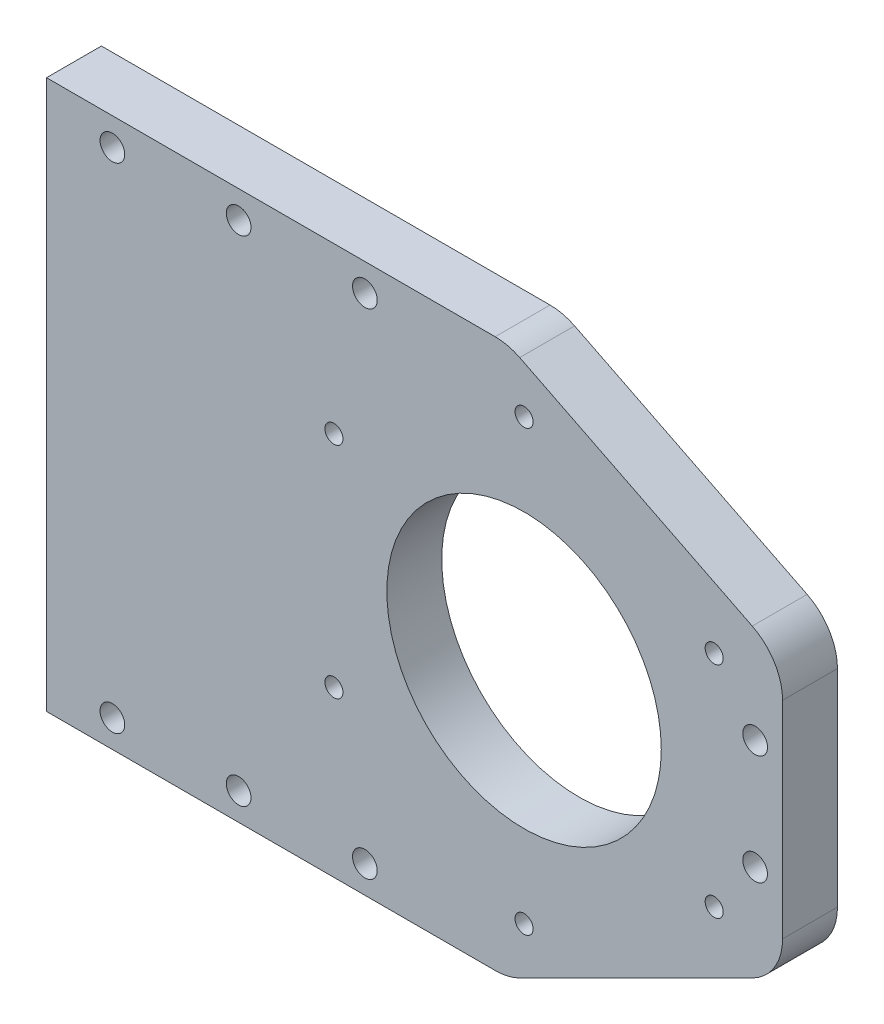
SolidWorks part; units mm, degrees
material "7079 Alloy"
ref_plane "Front Plane" through (0, 0, 0) normal (0, 0, 1) x (1, 0, 0)
ref_plane "Top Plane" through (0, 0, 0) normal (0, 1, 0) x (1, 0, 0)
ref_plane "Right Plane" through (0, 0, 0) normal (1, 0, 0) x (0, 0, -1)
sketch "Sketch1" plane through (0, 0, 0) normal (0, 0, 1) x (1, 0, 0)
  line L0 (0, 0) -> (84.1, 0) construction
  line L1 (0, -50) -> (84.1, -50)
  line L2 (84.1, 50) -> (134.1, 25)
  line L3 (0, -50) -> (0, 50)
  line L4 (0, 50) -> (84.1, 50)
  line L5 (134.1, -25) -> (134.1, 25)
  line L6 (84.1, -50) -> (134.1, -25)
  line L7 (84.1, 0) -> (84.1, -50) construction
  point P3 (134.1, 50)
  point P5 (134.1, -50)
  dimension "D1" = 134.1
  dimension "D2" = 100
  dimension "D3" = 25
  dimension "D4" = 25
extrude "Extrude1" add sketch "Sketch1" along normal blind 10
sketch "Sketch5" plane through (0, 0, 10) normal (0, 0, 1) x (1, 0, 0)
  line L0 (0, 0) -> (87, 0) construction
  circle A0 centre (87, 0) radius 25
  dimension "D2" = 50
  dimension "D1" = 87
extrude "Cut-Extrude1" cut sketch "Sketch5" against normal blind 20
sketch "Sketch6" plane through (0, 0, 0) normal (-1, 0, 0) x (0, 0, 1)
  line L0 (5, 50) -> (5, -50) construction
  line L1 (10, 50) -> (0, 50) construction
  line L2 (10, -50) -> (0, -50) construction
  line L3 (0, 0) -> (10, 0) construction
  line L4 (10, 50) -> (10, -50) construction
  circle A0 centre (5, 37.5) radius 1.65
  circle A1 centre (5, 12.5) radius 1.65
  circle A2 centre (5, -37.5) radius 1.65
  circle A3 centre (5, -12.5) radius 1.65
  dimension "D1" = 3.3
  dimension "D3" = 25
  dimension "D2" = 12.5
extrude "Cut-Extrude2" cut sketch "Sketch6" against normal blind 15
sketch "Sketch7" plane through (0, 0, 0) normal (0, 0, -1) x (-1, 0, 0)
  line L0 (0, 45) -> (-70, 45) construction
  line L1 (-84.1, 50) -> (0, 50) construction
  line L2 (0, 50) -> (0, -50) construction
  line L3 (-35, 45) -> (-35, 50) construction
  line L4 (0, 0) -> (-62, 0) construction
  circle A0 centre (-12, 45) radius 1.5
  circle A1 centre (-35, 45) radius 1.5
  circle A2 centre (-58, 45) radius 1.5
  circle A3 centre (-87, 0) radius 25 construction
  circle A4 centre (-58, -45) radius 1.5
  circle A5 centre (-35, -45) radius 1.5
  circle A6 centre (-12, -45) radius 1.5
  dimension "D2" = 3
  dimension "D1" = 12
  dimension "D3" = 23
  dimension "D4" = 5
extrude "Cut-Extrude3" cut sketch "Sketch7" against normal up to next
hole_wizard "CSK for M4 Flat Head Machine Screw1" positions "Sketch9" profile "Sketch8" countersink size "M4" standard "Ansi Metric" end condition through all
sketch "Sketch9" plane through (0, 0, 0) normal (0, 0, -1) x (-1, 0, 0)
  point P1 (-12, 45)
  point P4 (-35, 45)
  point P7 (-58, 45)
  point P10 (-12, -45)
  point P13 (-35, -45)
  point P16 (-58, -45)
sketch "Sketch8" plane through (12, 45, 0) normal (1, 0, 0) x (0, 1, 0)
  line L0 (0, 0) -> (0, 10)
  line L1 (0, 10) -> (2.25, 10)
  line L2 (2.25, 10) -> (2.25, 2.45)
  line L3 (2.25, 2.45) -> (4.7, 0)
  line L5 (4.7, 0) -> (0, 0)
  line L6 (-2.25, 2.45) -> (-4.7, 0) construction
  line L11 (0, -6.35) -> (0, 107.95) construction
  dimension "Thru Hole Dia." = 4.5
  dimension "Thru Hole Depth" = 10
  dimension "Near C'Sink Dia." = 9.4
  dimension "Near C'Sink Angle" = 90
sketch "Sketch10" plane through (0, 0, 0) normal (0, 0, -1) x (-1, 0, 0)
  line L0 (-87, 0) -> (-87, 40) construction
  circle A0 centre (-87, 0) radius 40 construction
  circle A1 centre (-87, 40) radius 1.65
  circle A2 centre (-52.359, 20) radius 1.65
  circle A3 centre (-52.359, -20) radius 1.65
  circle A4 centre (-87, -40) radius 1.65
  circle A5 centre (-121.641, -20) radius 1.65
  circle A6 centre (-121.641, 20) radius 1.65
  dimension "D2" = 3.3
  dimension "D3" = 80
  dimension "D1" = 6
extrude "Cut-Extrude4" cut sketch "Sketch10" against normal blind 10
fillet "Fillet1" radius 10 4 edges at (84.1, -50, 5) (134.1, -25, 5) (134.1, 25, 5) (84.1, 50, 5)
sketch "Sketch13" plane through (0, 0, 0) normal (0, 0, -1) x (-1, 0, 0)
  line L0 (-134.1, 0) -> (-129.1, 0) construction
  line L1 (-134.1, -18.8197) -> (-134.1, 18.8197) construction
  line L2 (-129.1, 0) -> (-129.1, 10) construction
  circle A0 centre (-129.1, 10) radius 2.25
  circle A1 centre (-129.1, -10) radius 2.25
  dimension "D3" = 4.5
  dimension "D1" = 10
  dimension "D2" = 5
extrude "Cut-Extrude5" cut sketch "Sketch13" against normal blind 10
hole_wizard "CSK for M4 Flat Head Machine Screw3" positions "Sketch15" profile "Sketch14" countersink size "M4" standard "Ansi Metric" end condition through all
sketch "Sketch15" plane through (0, 0, 0) normal (0, 0, -1) x (-1, 0, 0)
  point P1 (-129.1, 10)
  point P4 (-129.1, -10)
sketch "Sketch14" plane through (129.1, 10, 0) normal (1, 0, 0) x (0, 1, 0)
  line L0 (0, 0) -> (0, 10)
  line L1 (0, 10) -> (2.25, 10)
  line L2 (2.25, 10) -> (2.25, 2.45)
  line L3 (2.25, 2.45) -> (4.7, 0)
  line L5 (4.7, 0) -> (0, 0)
  line L6 (-2.25, 2.45) -> (-4.7, 0) construction
  line L11 (0, -6.35) -> (0, 107.95) construction
  dimension "Thru Hole Dia." = 4.5
  dimension "Thru Hole Depth" = 10
  dimension "Near C'Sink Dia." = 9.4
  dimension "Near C'Sink Angle" = 90
